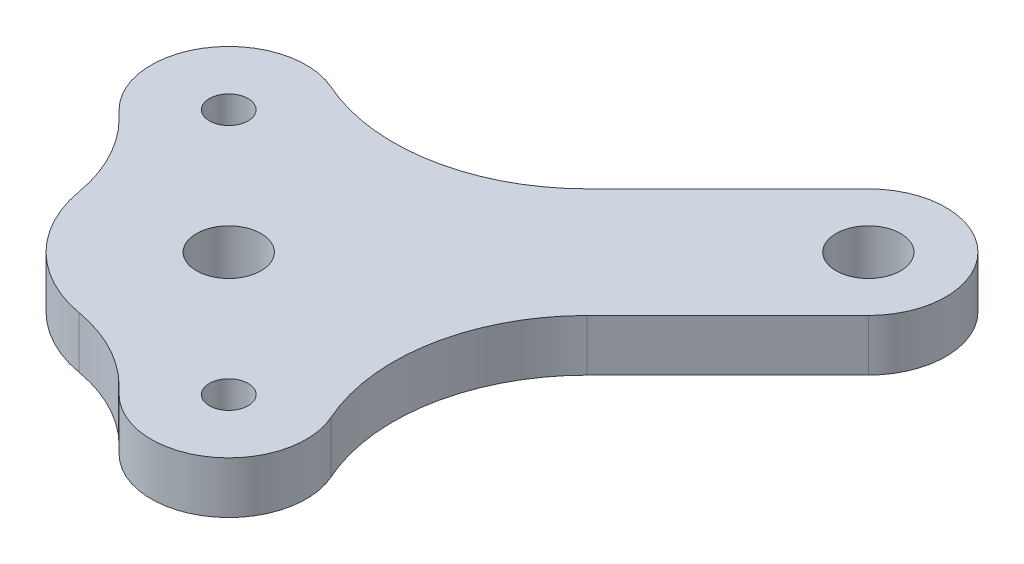
SolidWorks part; units mm, degrees
ref_plane "Plan de face" through (0, 0, 0) normal (0, 0, 1) x (1, 0, 0)
ref_plane "Plan de dessus" through (0, 0, 0) normal (0, 1, 0) x (1, 0, 0)
ref_plane "Plan de droite" through (0, 0, 0) normal (1, 0, 0) x (0, 0, -1)
sketch "Esquisse1" plane through (0, 29.5, 0) normal (0, 1, 0) x (1, 0, 0)
  line L0 (27.5, -70) -> (17.9541, -60.4541) construction
  line L1 (56.4914, -49.4939) -> (45.6126, -60.3727)
  line L2 (52.2487, -45.2513) -> (27.5, -70) construction
  line L3 (13.7114, -64.6967) -> (17.6005, -68.5858)
  line L4 (48.0061, -41.0086) -> (56.4914, -49.4939) construction
  line L5 (48.0061, -41.0086) -> (37.1273, -51.8874)
  line L6 (28.9142, -79.8995) -> (32.8033, -83.7886)
  line L8 (17.9541, -60.4541) -> (20.4017, -54.976) construction
  arc A0 (56.4914, -49.4939) -> (48.0061, -41.0086) centre (52.2487, -45.2513) ccw
  circle A1 centre (17.9541, -60.4541) radius 1.5
  arc A2 (20.4017, -54.976) -> (13.7114, -64.6967) centre (17.9541, -60.4541) ccw
  arc A3 (20.4017, -54.976) -> (37.1273, -51.8874) centre (26.5207, -41.2808) ccw
  circle A4 centre (37.0459, -79.5459) radius 1.5
  circle A5 centre (27.5, -70) radius 2.5
  arc A6 (42.524, -77.0983) -> (45.6126, -60.3727) centre (56.2192, -70.9793) cw
  arc A9 (42.524, -77.0983) -> (32.8033, -83.7886) centre (37.0459, -79.5459) cw
  circle A10 centre (52.2487, -45.2513) radius 2.5
  circle A11 centre (52.2487, -45.2513) radius 2.5 construction
  arc A12 (17.6005, -68.5858) -> (28.9142, -79.8995) centre (27.5, -70) ccw
  point P27 (27.5106, -69.9894)
  point P28 (27.5099, -69.9901)
  dimension "D1" = 12
  dimension "D2" = 15
  dimension "D5" = 5
  dimension "D6" = 3
  dimension "D3" = 12
  dimension "D7" = 20
  dimension "D4" = 13.5
extrude "Boss.-Extru.1" add sketch "Esquisse1" along normal mid plane 4
fillet "Congé1" radius 12 2 edges at (17.6005, 29.5, 68.5858) (28.9142, 29.5, 79.8995)
equation "\"M\"= 2"
